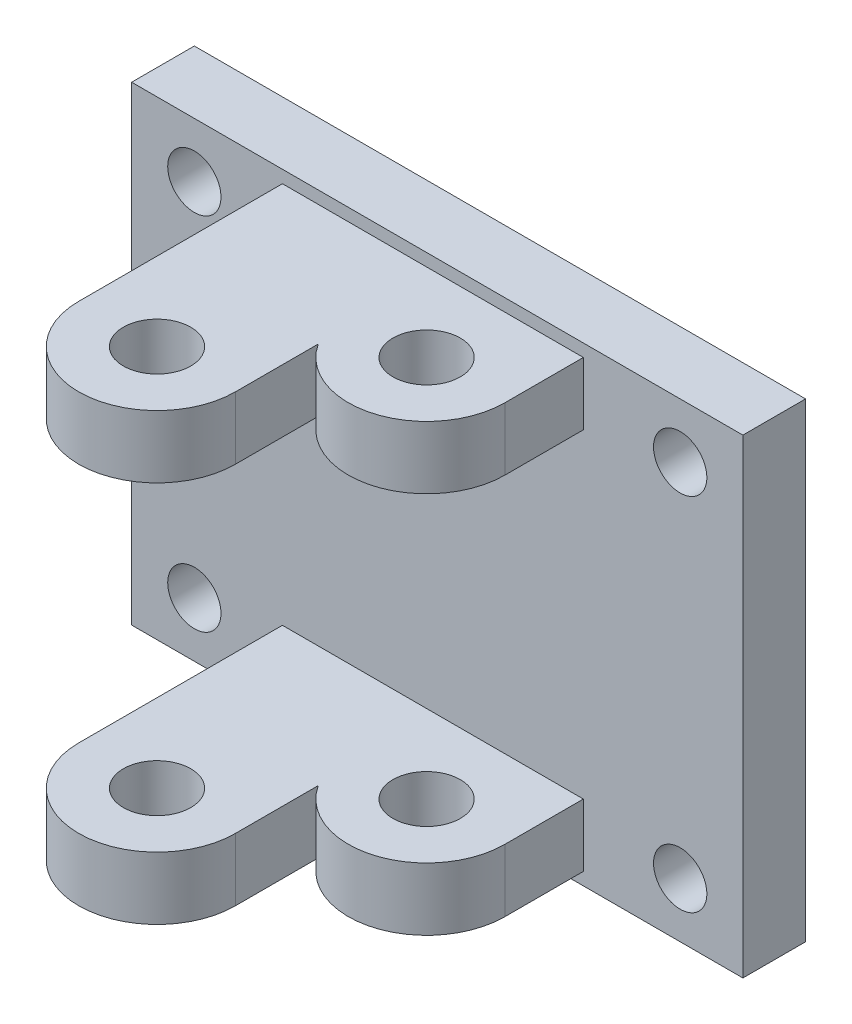
SolidWorks part; units mm, degrees
ref_plane "Front Plane" through (0, 0, 0) normal (0, 0, 1) x (1, 0, 0)
ref_plane "Top Plane" through (0, 0, 0) normal (0, 1, 0) x (1, 0, 0)
ref_plane "Right Plane" through (0, 0, 0) normal (1, 0, 0) x (0, 0, -1)
sketch "Removable_adapter_base_profile" plane through (0, 0, 0) normal (0, 0, 1) x (1, 0, 0)
  line L1 (23, -15) -> (62, -15)
  line L2 (23, -15) -> (23, 15)
  line L3 (23, 15) -> (62, 15)
  line L4 (62, -15) -> (62, 15)
  dimension "D1" = 39
  dimension "D2" = 30
  dimension "D3" = 23
  dimension "D4" = 15
extrude "Removable_adapter_base" add sketch "Removable_adapter_base_profile" along normal blind 4 from offset 4
sketch "Left_pin0_support_profile" plane through (0, 0, 0) normal (0, 1, 0) x (1, 0, 0)
  line L1 (32.6205, -21) -> (42.6205, -21)
  line L2 (32.6205, -21) -> (32.6205, -8)
  line L3 (32.6205, -8) -> (42.6205, -8)
  line L4 (42.6205, -21) -> (42.6205, -8)
  dimension "D1" = 10
  dimension "D2" = 13
  dimension "D3" = 32.6205
  dimension "D4" = 8
extrude "Left_pin0_support" add sketch "Left_pin0_support_profile" along normal blind 4 from offset 10.2
sketch "Left_pin0_rounded_lug_profile" plane through (0, 0, 0) normal (0, 1, 0) x (1, 0, 0)
  circle A0 centre (37.6205, -21) radius 5
  dimension "D1" = 10
  dimension "D2" = 37.6205
  dimension "D3" = 21
extrude "Left_pin0_rounded_lug" add sketch "Left_pin0_rounded_lug_profile" along normal blind 4 from offset 10.2
sketch "Left_pin1_support_profile" plane through (0, 0, 0) normal (0, 1, 0) x (1, 0, 0)
  line L1 (41.8205, -13) -> (51.8205, -13)
  line L2 (41.8205, -13) -> (41.8205, -8)
  line L3 (41.8205, -8) -> (51.8205, -8)
  line L4 (51.8205, -13) -> (51.8205, -8)
  dimension "D1" = 10
  dimension "D2" = 5
  dimension "D3" = 41.8205
  dimension "D4" = 8
extrude "Left_pin1_support" add sketch "Left_pin1_support_profile" along normal blind 4 from offset 10.2
sketch "Left_pin1_rounded_lug_profile" plane through (0, 0, 0) normal (0, 1, 0) x (1, 0, 0)
  circle A0 centre (46.8205, -13) radius 5
  dimension "D1" = 10
  dimension "D2" = 46.8205
  dimension "D3" = 13
extrude "Left_pin1_rounded_lug" add sketch "Left_pin1_rounded_lug_profile" along normal blind 4 from offset 10.2
sketch "Right_pin0_support_profile" plane through (0, 0, 0) normal (0, 1, 0) x (1, 0, 0)
  line L1 (32.6205, -21) -> (42.6205, -21)
  line L2 (32.6205, -21) -> (32.6205, -8)
  line L3 (32.6205, -8) -> (42.6205, -8)
  line L4 (42.6205, -21) -> (42.6205, -8)
  dimension "D1" = 10
  dimension "D2" = 13
  dimension "D3" = 32.6205
  dimension "D4" = 8
extrude "Right_pin0_support" add sketch "Right_pin0_support_profile" along normal blind 4 from offset 14.2
sketch "Right_pin0_rounded_lug_profile" plane through (0, 0, 0) normal (0, 1, 0) x (1, 0, 0)
  circle A0 centre (37.6205, -21) radius 5
  dimension "D1" = 10
  dimension "D2" = 37.6205
  dimension "D3" = 21
extrude "Right_pin0_rounded_lug" add sketch "Right_pin0_rounded_lug_profile" along normal blind 4 from offset 14.2
sketch "Right_pin1_support_profile" plane through (0, 0, 0) normal (0, 1, 0) x (1, 0, 0)
  line L1 (41.8205, -13) -> (51.8205, -13)
  line L2 (41.8205, -13) -> (41.8205, -8)
  line L3 (41.8205, -8) -> (51.8205, -8)
  line L4 (51.8205, -13) -> (51.8205, -8)
  dimension "D1" = 10
  dimension "D2" = 5
  dimension "D3" = 41.8205
  dimension "D4" = 8
extrude "Right_pin1_support" add sketch "Right_pin1_support_profile" along normal blind 4 from offset 14.2
sketch "Right_pin1_rounded_lug_profile" plane through (0, 0, 0) normal (0, 1, 0) x (1, 0, 0)
  circle A0 centre (46.8205, -13) radius 5
  dimension "D1" = 10
  dimension "D2" = 46.8205
  dimension "D3" = 13
extrude "Right_pin1_rounded_lug" add sketch "Right_pin1_rounded_lug_profile" along normal blind 4 from offset 14.2
sketch "Both_M4_gripper_pin_axes_profile" plane through (0, 0, 0) normal (0, 1, 0) x (1, 0, 0)
  circle A0 centre (37.6205, -21) radius 2.15
  circle A1 centre (46.8205, -13) radius 2.15
  dimension "D1" = 4.3
  dimension "D2" = 4.3
  dimension "D3" = 37.6205
  dimension "D4" = 46.8205
  dimension "D5" = 13
  dimension "D6" = 21
extrude "Both_M4_gripper_pin_axes" cut sketch "Both_M4_gripper_pin_axes_profile" along normal through all from offset 20
sketch "Four_M3_removable_deck_bolts_profile" plane through (0, 0, 0) normal (0, 0, 1) x (1, 0, 0)
  circle A0 centre (27, -11.5) radius 1.7
  circle A1 centre (27, 11.5) radius 1.7
  circle A2 centre (58, -11.5) radius 1.7
  circle A3 centre (58, 11.5) radius 1.7
  dimension "D1" = 3.4
  dimension "D2" = 3.4
  dimension "D3" = 3.4
  dimension "D4" = 3.4
  dimension "D5" = 27
  dimension "D6" = 58
  dimension "D7" = 11.5
  dimension "D8" = 11.5
extrude "Four_M3_removable_deck_bolts" cut sketch "Four_M3_removable_deck_bolts_profile" along normal through all from offset 50
